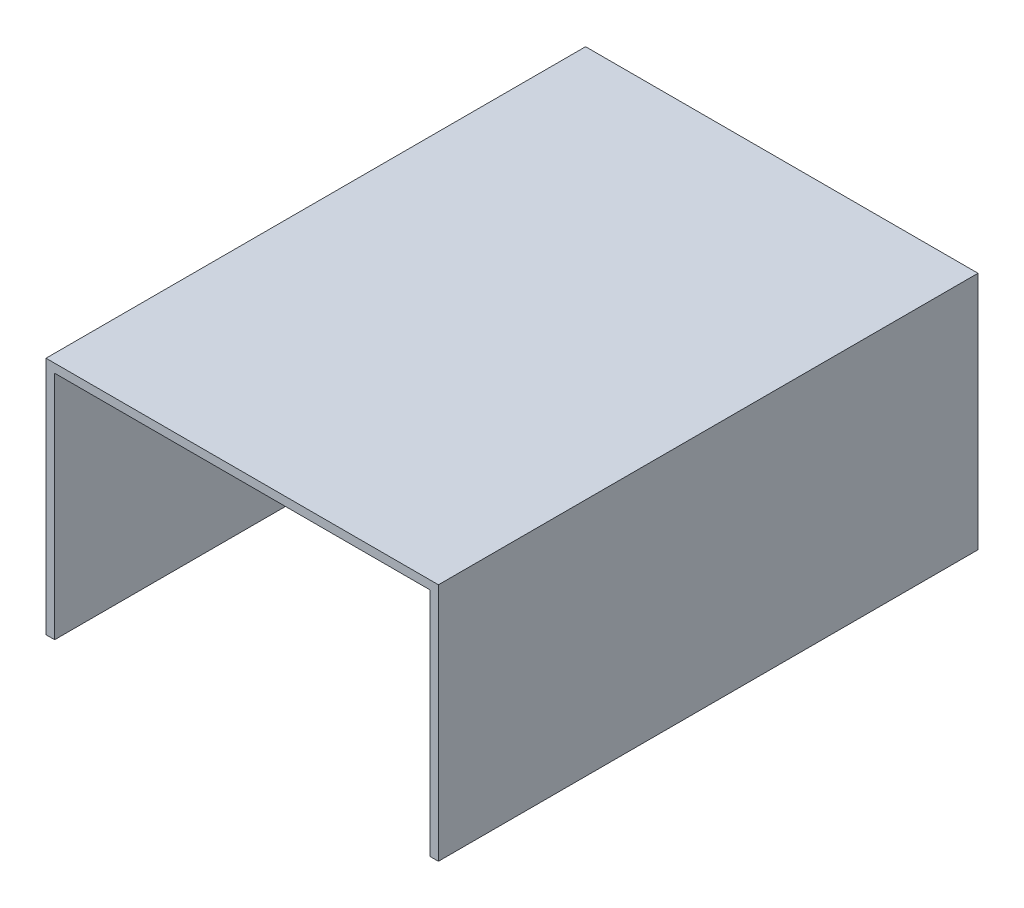
SolidWorks part; units mm, degrees
ref_plane "Plano frontal" through (0, 0, 0) normal (0, 0, 1) x (1, 0, 0)
ref_plane "Plano superior" through (0, 0, 0) normal (0, 1, 0) x (1, 0, 0)
ref_plane "Plano direito" through (0, 0, 0) normal (1, 0, 0) x (0, 0, -1)
sketch "Esboço1" plane through (0, 0, 0) normal (0, 0, 1) x (1, 0, 0)
  line L1 (6.8, -4.15) -> (-6.8, -4.15)
  line L2 (6.8, -4.15) -> (6.8, 4.15)
  line L3 (6.8, 4.15) -> (-6.8, 4.15)
  line L4 (-6.8, -4.15) -> (-6.8, 4.15)
  line L5 (6.8, -4.15) -> (-6.8, 4.15) construction
  line L6 (6.8, 4.15) -> (-6.8, -4.15) construction
  point P0 (0, 0)
  dimension "D1" = 13.6
  dimension "D2" = 8.3
extrude "Ressalto-extrusão1" add sketch "Esboço1" along normal blind 18.7 contours L2 L1 L4 L3
sketch "Esboço4" plane through (0, 0, 18.7) normal (0, 0, 1) x (1, 0, 0)
  line L0 (-6.5, 3.85) -> (-6.5, -4.15)
  line L5 (6.5, -3.85) -> (-6.5, 3.85) construction
  line L6 (6.5, 3.85) -> (-6.5, -3.85) construction
  line L7 (6.8, -4.15) -> (-6.8, -4.15) construction
  line L8 (-6.5, -4.15) -> (6.5, -4.15)
  line L9 (6.5, -4.15) -> (6.5, 3.85)
  line L10 (6.5, 3.85) -> (-6.5, 3.85)
  point P0 (0, 0)
extrude "Corte-extrusão1" cut sketch "Esboço4" against normal blind 18.1 and the other way through all
sketch "Esboço5" plane through (0, 0, 0) normal (0, 0, -1) x (-1, 0, 0)
  circle A0 centre (0, 0) radius 1.4
  dimension "D1" = 2.8
extrude "Corte-extrusão2" cut sketch "Esboço5" against normal up to next
